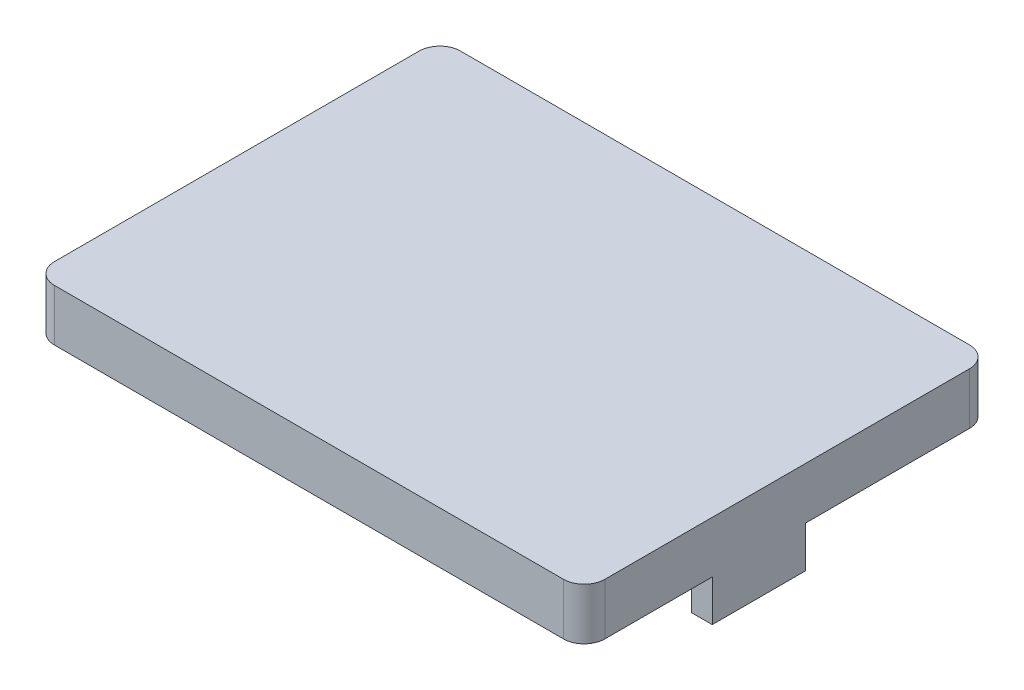
SolidWorks part; units mm, degrees
ref_plane "Front Plane" through (0, 0, 0) normal (0, 0, 1) x (1, 0, 0)
ref_plane "Top Plane" through (0, 0, 0) normal (0, 1, 0) x (1, 0, 0)
ref_plane "Right Plane" through (0, 0, 0) normal (1, 0, 0) x (0, 0, -1)
sketch "Sketch1" plane through (0, 0, 0) normal (0, 1, 0) x (1, 0, 0)
  line L1 (-26.63, 19.645) -> (26.63, 19.645)
  line L2 (-26.63, 19.645) -> (-26.63, -19.645)
  line L3 (-26.63, -19.645) -> (26.63, -19.645)
  line L4 (26.63, 19.645) -> (26.63, -19.645)
  line L5 (-26.63, 19.645) -> (26.63, -19.645) construction
  line L6 (-26.63, -19.645) -> (26.63, 19.645) construction
  point P0 (0, 0)
  dimension "D1" = 53.26
  dimension "D2" = 39.29
extrude "Boss-Extrude1" add sketch "Sketch1" along normal blind 5
fillet "Fillet1" radius 2 4 edges at (26.63, 2.5, -19.645) (26.63, 2.5, 19.645) (-26.63, 2.5, -19.645) (-26.63, 2.5, 19.645)
sketch "Sketch2" plane through (0, 0, 0) normal (0, -1, 0) x (-1, 0, 0)
  circle A0 centre (23.03, -16.045) radius 2.55
  circle A1 centre (23.03, 16.045) radius 2.55
extrude "Cut-Extrude1" cut sketch "Sketch2" against normal blind 4.1
sketch "Sketch3" plane through (0, 0, 0) normal (0, -1, 0) x (-1, 0, 0)
  line L6 (-26.63, -17.645) -> (-26.63, 17.645) construction
  line L7 (-26.63, 1.752) -> (-24.63, 1.752)
  line L8 (-26.63, 1.752) -> (-26.63, -7.248)
  line L9 (-26.63, -7.248) -> (-24.63, -7.248)
  line L10 (-24.63, 1.752) -> (-24.63, -7.248)
  line L11 (-28.186, 1.752) -> (-16.686, 1.752) construction
  line L12 (-24.63, -17.645) -> (-24.63, 17.645) construction
  line L13 (-16.686, -7.248) -> (-28.186, -7.248) construction
extrude "Boss-Extrude2" add sketch "Sketch3" along normal blind 4
